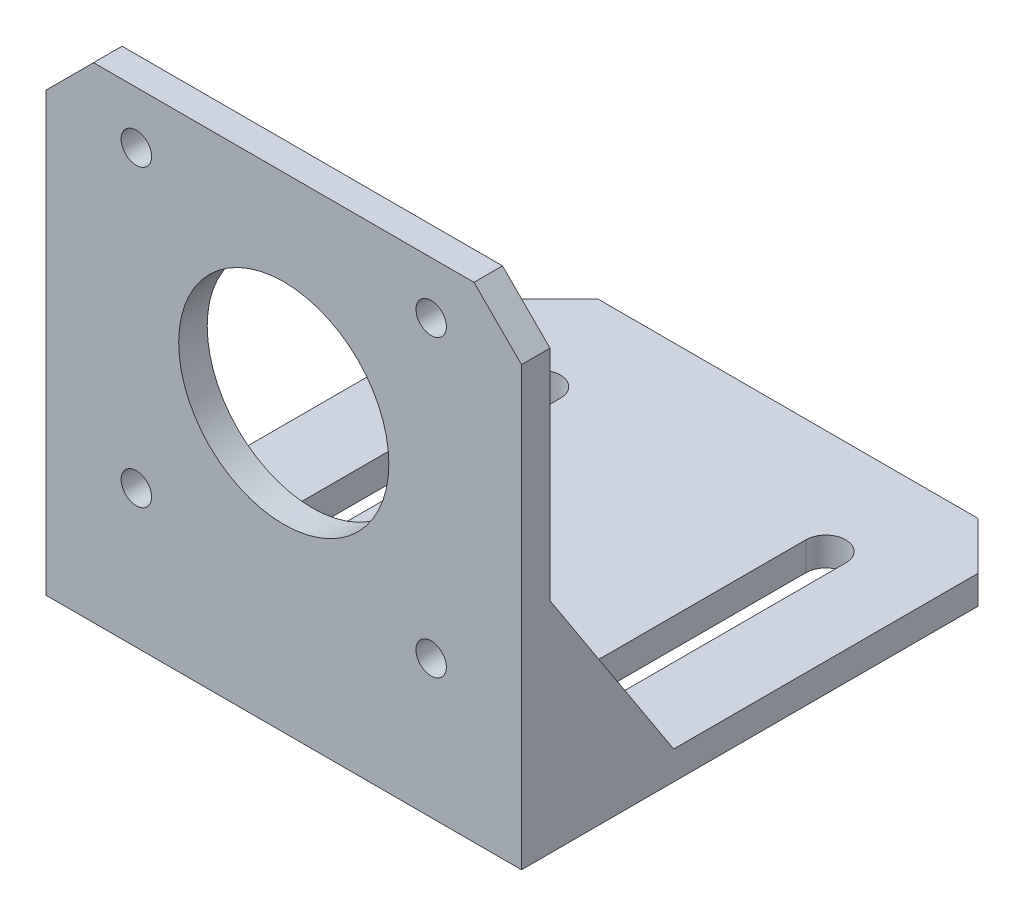
SolidWorks part; units mm, degrees
ref_plane "前视基准面" through (0, 0, 0) normal (0, 0, 1) x (1, 0, 0)
ref_plane "上视基准面" through (0, 0, 0) normal (0, 1, 0) x (1, 0, 0)
ref_plane "右视基准面" through (0, 0, 0) normal (1, 0, 0) x (0, 0, -1)
other "Configuration Table"
sketch "草图1" plane through (0, 0, 0) normal (1, 0, 0) x (0, 0, -1)
  line L1 (0, 0) -> (53, 0)
  line L2 (0, 0) -> (0, -51)
  line L3 (0, -51) -> (53, -51)
  line L4 (53, 0) -> (53, -51)
  line L7 (53, -48) -> (16, -48)
  line L8 (3, 0.449) -> (3, -28)
  line L10 (3, -28) -> (16, -48)
  dimension "D1" = 51
  dimension "D2" = 53
  dimension "D3" = 3
  dimension "D4" = 3
extrude "凸台-拉伸1" add sketch "草图1" along normal blind 50
sketch "草图4" plane through (0, -48, 0) normal (0, 1, 0) x (1, 0, 0)
  line L0 (50, 16) -> (0, 16) construction
  line L1 (3, 16) -> (47, 16)
  line L2 (3, 16) -> (3, 3)
  line L3 (3, 3) -> (47, 3)
  line L4 (47, 16) -> (47, 3)
  line L5 (50, 3) -> (0, 3) construction
  line L6 (50, 3) -> (50, 16) construction
  line L7 (0, 3) -> (0, 16) construction
  dimension "D1" = 3
  dimension "D2" = 3
extrude "切除-拉伸2" cut sketch "草图4" along normal blind 20
sketch "草图5" plane through (0, -48, 0) normal (0, 1, 0) x (1, 0, 0)
  line L0 (50, 53) -> (50, 16) construction
  line L1 (0, 53) -> (0, 16) construction
  line L2 (50, 53) -> (0, 53) construction
  line L3 (50, 53) -> (50, 16) construction
  line L4 (0, 53) -> (0, 16) construction
  line L5 (50, 53) -> (0, 53) construction
  line L6 (25, 53) -> (25, 3) construction
  line L7 (50, 3) -> (0, 3) construction
  line L8 (10, 42) -> (10, 12) construction
  line L9 (12.1, 42) -> (12.1, 12)
  line L10 (7.9, 42) -> (7.9, 12)
  line L11 (40, 42) -> (40, 12) construction
  line L12 (37.9, 42) -> (37.9, 12)
  line L13 (42.1, 42) -> (42.1, 12)
  line L14 (50, 53) -> (45, 53)
  line L15 (5, 53) -> (0, 48)
  line L16 (0, 48) -> (0, 53)
  line L17 (0, 53) -> (5, 53)
  line L18 (50, 48) -> (50, 53)
  line L19 (45, 53) -> (50, 48)
  arc A0 (12.1, 42) -> (7.9, 42) centre (10, 42) ccw
  arc A1 (7.9, 12) -> (12.1, 12) centre (10, 12) ccw
  arc A2 (37.9, 42) -> (42.1, 42) centre (40, 42) cw
  arc A3 (42.1, 12) -> (37.9, 12) centre (40, 12) cw
  point P10 (10, 27)
  point P17 (40, 27)
  dimension "D1" = 15
  dimension "D2" = 30
  dimension "D3" = 11
  dimension "D4" = 4.2
  dimension "D5" = 5
  dimension "D6" = 5
extrude "切除-拉伸3" cut sketch "草图5" against normal through all
sketch "草图6" plane through (0, 0, -3) normal (0, 0, -1) x (-1, 0, 0)
  line L0 (-50, 0) -> (0, 0) construction
  line L5 (-50, 0) -> (-50, -5)
  line L6 (-40.5, -5.5) -> (-9.5, -5.5) construction
  line L7 (-40.5, -5.5) -> (-40.5, -36.5) construction
  line L8 (-40.5, -36.5) -> (-9.5, -36.5) construction
  line L9 (-9.5, -5.5) -> (-9.5, -36.5) construction
  line L10 (-40.5, -5.5) -> (-9.5, -36.5) construction
  line L11 (-40.5, -36.5) -> (-9.5, -5.5) construction
  line L12 (-50, 0) -> (-50, -28) construction
  line L13 (-50, -5) -> (-45, 0)
  line L14 (-45, 0) -> (-50, 0)
  line L15 (0, 0) -> (0, -28) construction
  line L16 (-25, 0) -> (-25, -21) construction
  line L17 (0, -5) -> (-5, 0)
  line L18 (0, 0) -> (0, -5)
  line L19 (-5, 0) -> (0, 0)
  circle A0 centre (-25, -21) radius 11.05
  circle A1 centre (-40.5, -5.5) radius 1.6
  circle A2 centre (-9.5, -5.5) radius 1.6
  circle A3 centre (-9.5, -36.5) radius 1.6
  circle A4 centre (-40.5, -36.5) radius 1.6
  dimension "D2" = 22.1
  dimension "D5" = 3.2
  dimension "D1" = 21
  dimension "D3" = 31
  dimension "D4" = 31
  dimension "D8" = 5
  dimension "D9" = 5
  dimension "D10" = 25
  dimension "D6" = 2
  dimension "D7" = 2
extrude "切除-拉伸4" cut sketch "草图6" against normal through all
